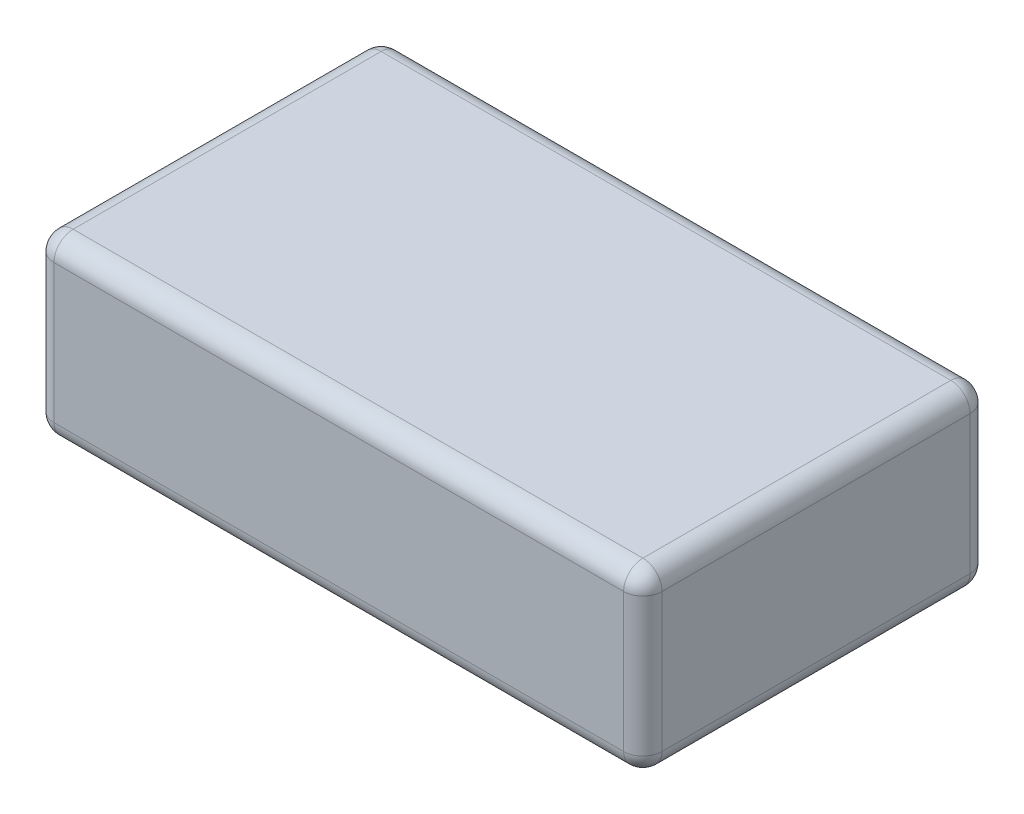
SolidWorks part; units mm, degrees
ref_plane "Front Plane" through (0, 0, 0) normal (0, 0, 1) x (1, 0, 0)
ref_plane "Top Plane" through (0, 0, 0) normal (0, 1, 0) x (1, 0, 0)
ref_plane "Right Plane" through (0, 0, 0) normal (1, 0, 0) x (0, 0, -1)
sketch "Sketch1" plane through (0, 0, 0) normal (0, 1, 0) x (1, 0, 0)
  line L1 (0, 0) -> (158, 0)
  line L2 (0, 0) -> (0, 90)
  line L3 (0, 90) -> (158, 90)
  line L4 (158, 0) -> (158, 90)
  dimension "D1" = 90
  dimension "D2" = 158
extrude "Boss-Extrude1" add sketch "Sketch1" along normal blind 46
fillet "Fillet2" radius 5 12 edges at (158, 23, 0) (158, 23, -90) (0, 23, -90) (0, 23, 0) (79, 0, 0) (158, 0, -45) (79, 0, -90) (0, 0, -45) (79, 46, -90) (158, 46, -45) (79, 46, 0) (0, 46, -45)
